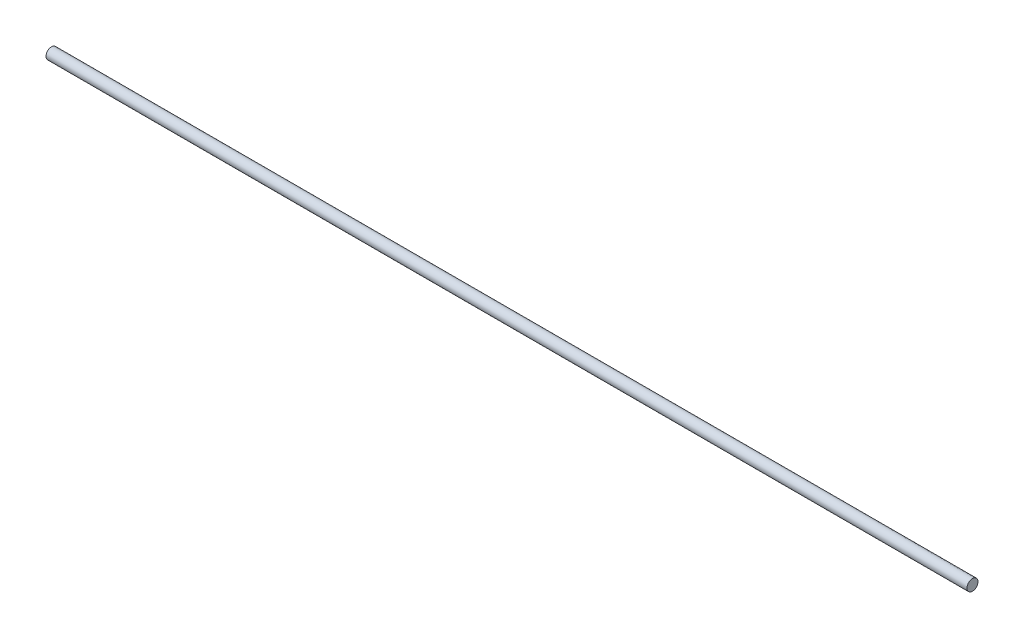
SolidWorks part; units mm, degrees
ref_plane "Front Plane" through (0, 0, 0) normal (0, 0, 1) x (1, 0, 0)
ref_plane "Top Plane" through (0, 0, 0) normal (0, 1, 0) x (1, 0, 0)
ref_plane "Right Plane" through (0, 0, 0) normal (1, 0, 0) x (0, 0, -1)
sketch "Sketch1" plane through (0, 0, 0) normal (1, 0, 0) x (0, 0, -1)
  circle A0 centre (0, 0) radius 1.5
  dimension "D1" = 3
extrude "Boss-Extrude1" add sketch "Sketch1" along normal blind 250
